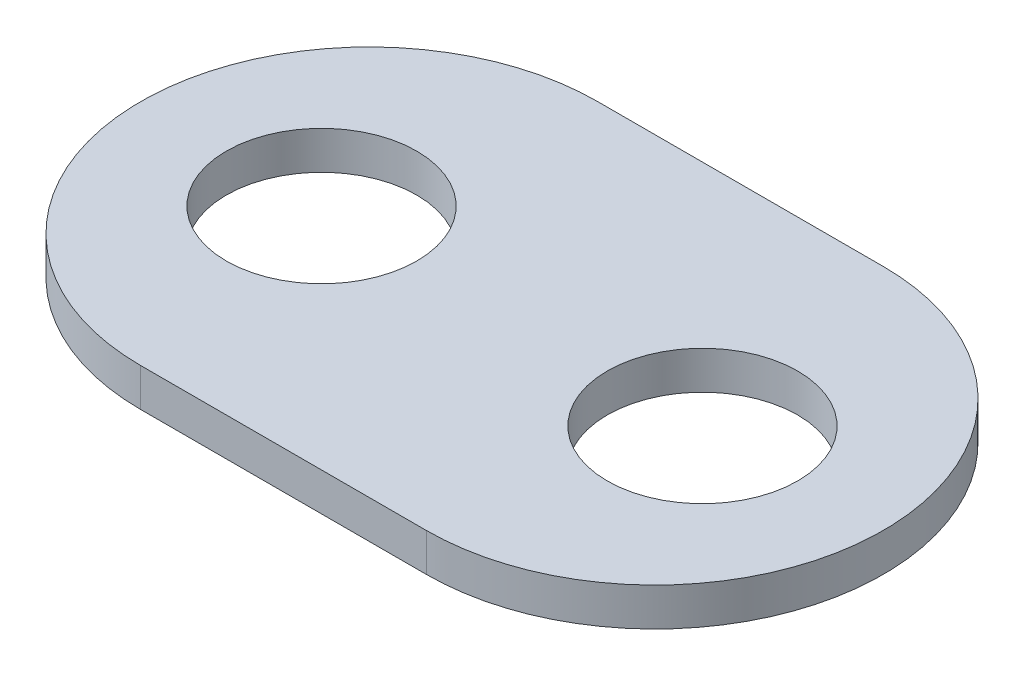
SolidWorks part; units mm, degrees
ref_plane "Front Plane" through (0, 0, 0) normal (0, 0, 1) x (1, 0, 0)
ref_plane "Top Plane" through (0, 0, 0) normal (0, 1, 0) x (1, 0, 0)
ref_plane "Right Plane" through (0, 0, 0) normal (1, 0, 0) x (0, 0, -1)
sketch "Sketch1" plane through (0, 0, 0) normal (0, 1, 0) x (1, 0, 0)
  line L0 (-7.5, -12) -> (7.5, -12)
  line L3 (-7.5, 12) -> (7.5, 12)
  line L4 (-10, 0) -> (10, 0) construction
  circle A2 centre (10, 0) radius 5
  circle A3 centre (-10, 0) radius 5
  circle A4 centre (-10, 0) radius 2.5
  circle A5 centre (10, 0) radius 2.5
  arc A6 (-7.5, 12) -> (-7.5, -12) centre (-7.5, 0) ccw
  arc A7 (7.5, 12) -> (7.5, -12) centre (7.5, 0) cw
  point P6 (0, -12)
  point P15 (0, 0)
  dimension "D3" = 10
  dimension "D4" = 10
  dimension "D5" = 5
  dimension "D6" = 5
  dimension "D7" = 12
  dimension "D10" = 20
  dimension "D2" = 12
  dimension "D8" = 15
  dimension "D9" = 15
  dimension "D11" = 10
extrude "Boss-Extrude1" add sketch "Sketch1" along normal blind 2
